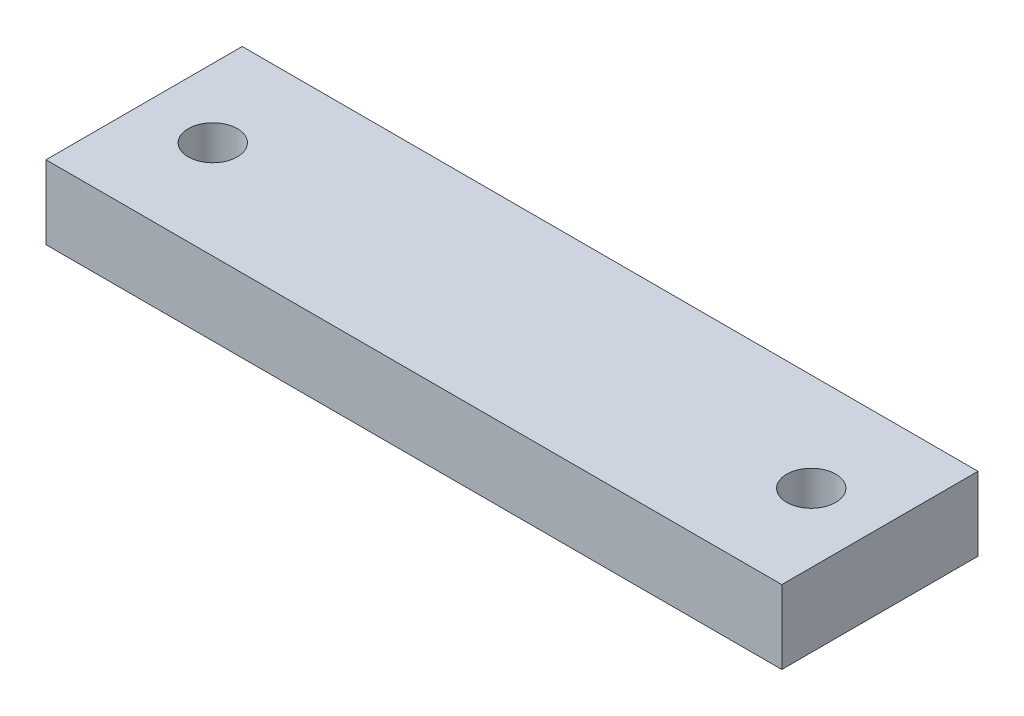
SolidWorks part; units mm, degrees
material "6061-T6 (SS)"
ref_plane "Front Plane" through (0, 0, 0) normal (0, 0, 1) x (1, 0, 0)
ref_plane "Top Plane" through (0, 0, 0) normal (0, 1, 0) x (1, 0, 0)
ref_plane "Right Plane" through (0, 0, 0) normal (1, 0, 0) x (0, 0, -1)
sketch "Sketch1" plane through (0, 0, 0) normal (0, 1, 0) x (1, 0, 0)
  line L1 (0, 0) -> (300, 0)
  line L2 (0, 0) -> (0, 80)
  line L3 (0, 80) -> (300, 80)
  line L4 (300, 0) -> (300, 80)
  dimension "D1" = 80
  dimension "D2" = 300
extrude "Boss-Extrude1" add sketch "Sketch1" along normal blind 30
sketch "Sketch2" plane through (0, 30, 0) normal (0, 1, 0) x (1, 0, 0)
  line L0 (0, 40) -> (300, 40) construction
  line L1 (0, 80) -> (0, 0) construction
  line L2 (300, 0) -> (300, 80) construction
  line L5 (150, 80) -> (150, 0) construction
  line L6 (300, 80) -> (0, 80) construction
  line L7 (0, 0) -> (300, 0) construction
  circle A0 centre (28, 40) radius 10
  circle A1 centre (272, 40) radius 10
  dimension "D1" = 20
  dimension "D2" = 20
  dimension "D3" = 244
extrude "Cut-Extrude1" cut sketch "Sketch2" against normal through all
equation "\"length\"= 300"
equation "\"length_hole\"=244"
equation "\"height\"= 30"
equation "\"diameter\"= 20"
equation "\"width\"= 80"
equation "\"D1@Sketch1\"=\"width\""
equation "\"D2@Sketch1\"=\"length\""
equation "\"D1@Sketch2\"=\"diameter\""
equation "\"D2@Sketch2\"=\"diameter\""
equation "\"D3@Sketch2\"=\"length_hole\""
equation "\"D1@Boss-Extrude1\"=\"height\""
